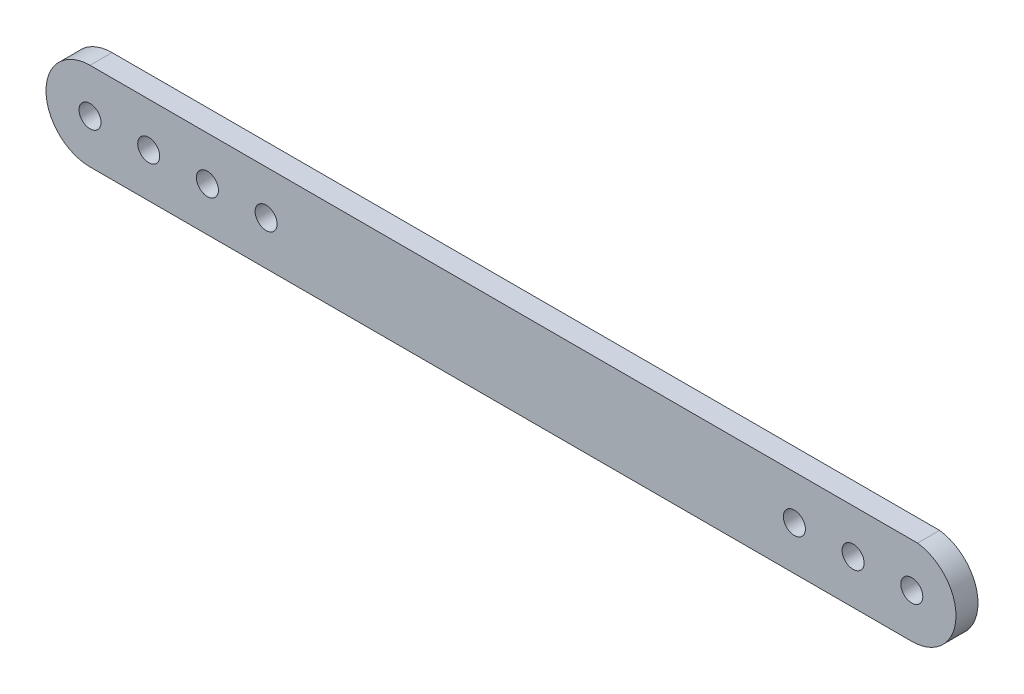
SolidWorks part; units mm, degrees
ref_plane "Front Plane" through (0, 0, 0) normal (0, 0, 1) x (1, 0, 0)
ref_plane "Top Plane" through (0, 0, 0) normal (0, 1, 0) x (1, 0, 0)
ref_plane "Right Plane" through (0, 0, 0) normal (1, 0, 0) x (0, 0, -1)
sketch "Sketch1" plane through (0, 0, 0) normal (0, 0, 1) x (1, 0, 0)
  line L1 (0, 9.525) -> (179.0557, 9.525)
  line L3 (0, -9.525) -> (177.7999, -9.525)
  arc A0 (0, 9.525) -> (0, -9.525) centre (0, 0) ccw
  arc A1 (177.7999, -9.525) -> (179.0557, 9.525) centre (177.7999, 0.0414) ccw
  circle A2 centre (0, 0) radius 2.3813
  circle A3 centre (12.7, 0) radius 2.3813
  circle A4 centre (25.4, 0) radius 2.3813
  circle A5 centre (38.1, 0) radius 2.3812
  circle A6 centre (177.7999, 0.0414) radius 2.3813
  circle A7 centre (165.1, 0) radius 2.3813
  circle A8 centre (152.4, 0) radius 2.3813
  dimension "D2" = 4.7625
  dimension "D3" = 4.7625
  dimension "D4" = 4.7625
  dimension "D5" = 4.7625
  dimension "D6" = 4.7625
  dimension "D7" = 4.7625
  dimension "D8" = 4.7625
  dimension "D15" = 9.525
  dimension "D16" = 9.5664
  dimension "D1" = 19.05
  dimension "D9" = 165.1
  dimension "D10" = 12.7
  dimension "D11" = 12.7
  dimension "D12" = 12.7
  dimension "D13" = 12.7
  dimension "D14" = 12.7
extrude "Boss-Extrude1" add sketch "Sketch1" along normal blind 4.7625
